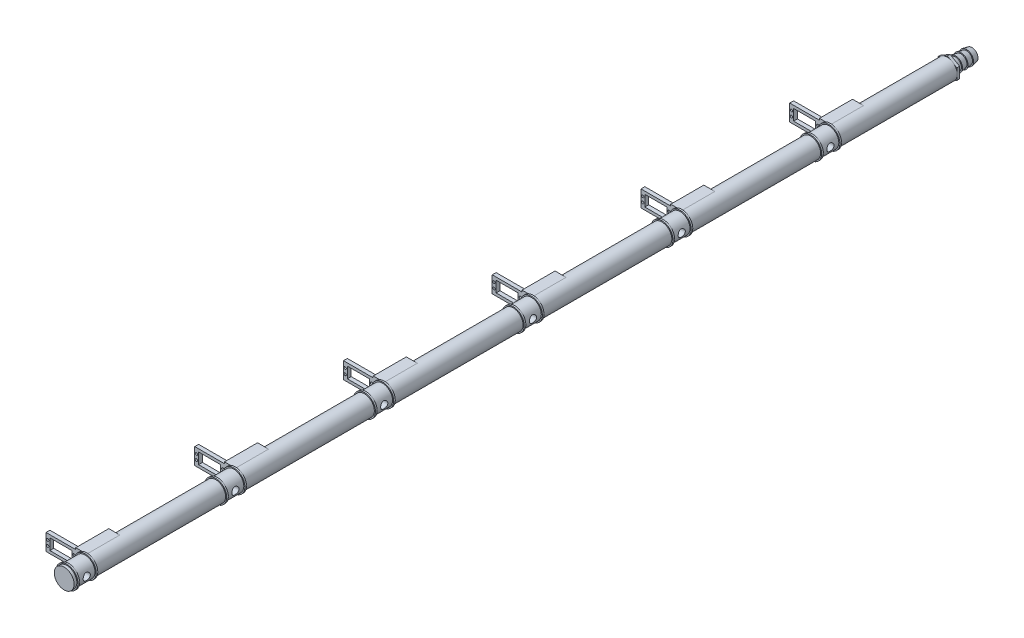
SolidWorks part; units mm, degrees
ref_plane "Front Plane" through (0, 0, 0) normal (0, 0, 1) x (1, 0, 0)
ref_plane "Top Plane" through (0, 0, 0) normal (0, 1, 0) x (1, 0, 0)
ref_plane "Right Plane" through (0, 0, 0) normal (1, 0, 0) x (0, 0, -1)
sketch "Sketch1" plane through (0, 0, 0) normal (0, 0, 1) x (1, 0, 0)
  circle A0 centre (0, 0) radius 15
  circle A1 centre (0, 0) radius 18
extrude "Boss-Extrude1" add sketch "Sketch1" along normal blind 1600
sketch "Sketch2" plane through (0, 0, 1600) normal (0, 0, 1) x (1, 0, 0)
  circle A0 centre (0, 0) radius 18
extrude "Boss-Extrude2" add sketch "Sketch2" along normal blind 3
sketch "Sketch3" plane through (0, 0, 0) normal (1, 0, 0) x (0, 0, -1)
  line L0 (-1603, 0) -> (-1600, 0) construction
  line L1 (-1603, 18) -> (-1603, -18) construction
  line L2 (-1600, 0) -> (-1600, 28.0213) construction
  line L3 (-1600, 0) -> (-100, 0) construction
  line L4 (-1600, 0) -> (-1580, 0) construction
  circle A0 centre (-1580, 0) radius 10
  circle A1 centre (-1310, 0) radius 10
  circle A2 centre (-1040, 0) radius 10
  circle A3 centre (-770, 0) radius 10
  circle A4 centre (-500, 0) radius 10
  circle A5 centre (-230, 0) radius 10
  dimension "D2" = 6
  dimension "D1" = 20
extrude "Cut-Extrude1" cut sketch "Sketch3" along normal through all
sketch "Sketch4" plane through (0, 0, 0) normal (1, 0, 0) x (0, 0, -1)
  line L0 (-1580, 0) -> (-1598, 0) construction
  line L2 (-1600, 0) -> (-100, 0) construction
  line L3 (-1598, 0) -> (-1562, 0) construction
ref_plane "Plane1" through (0, 0, 1598) normal (0, 0, 1) x (1, 0, 0)
sketch "Sketch5" plane through (0, 0, 1598) normal (0, 0, 1) x (1, 0, 0)
  circle A0 centre (0, 0) radius 18
  circle A1 centre (0, 0) radius 20
extrude "Boss-Extrude3" add sketch "Sketch5" against normal blind 3
pattern_linear "LPattern1" count 6 spacing 270 along (0, 0, -1) of "Boss-Extrude3"
ref_plane "Plane2" through (0, 0, 1562) normal (0, 0, 1) x (1, 0, 0)
sketch "Sketch6" plane through (0, 0, 1562) normal (0, 0, 1) x (1, 0, 0)
  circle A0 centre (0, 0) radius 20 construction
  circle A1 centre (0, 0) radius 20
  circle A2 centre (0, 0) radius 18 construction
  circle A3 centre (0, 0) radius 18
extrude "Boss-Extrude4" add sketch "Sketch6" along normal blind 3
pattern_linear "LPattern2" count 6 spacing 270 along (0, 0, -1) of "Boss-Extrude4"
sketch "Sketch7" plane through (0, 0, 0) normal (0, 0, -1) x (-1, 0, 0)
  line L1 (0, 20) -> (-17.3205, 10)
  line L2 (-17.3205, 10) -> (-17.3205, -10)
  line L3 (-17.3205, -10) -> (0, -20)
  line L4 (0, -20) -> (17.3205, -10)
  line L5 (17.3205, -10) -> (17.3205, 10)
  line L6 (17.3205, 10) -> (0, 20)
  circle A0 centre (0, 0) radius 17.3205 construction
extrude "Boss-Extrude5" add sketch "Sketch7" along normal blind 5 separate body
sketch "Sketch8" plane through (0, 0, 0) normal (1, 0, 0) x (0, 0, -1)
  line L0 (5, 0) -> (44.7107, 0) construction
  line L1 (5, 10) -> (5, -10) construction
  line L2 (44.7107, 0) -> (44.7107, 6) construction
  line L3 (44.7107, 6) -> (5, 6)
  line L4 (44.7107, 6) -> (44.7107, 11)
  line L5 (44.7107, 11) -> (34.7107, 11) construction
  line L6 (34.7107, 11) -> (34.7107, 13) construction
  line L7 (44.7107, 11) -> (34.7107, 13)
  line L8 (34.7107, 13) -> (34.7107, 11)
  line L9 (34.7107, 11) -> (24.7107, 13)
  line L10 (24.7107, 13) -> (24.7107, 11)
  line L11 (24.7107, 11) -> (14.7107, 13)
  line L12 (14.7107, 13) -> (14.7107, 11)
  line L13 (14.7107, 11) -> (5, 12.9421)
  line L15 (5, 6) -> (5, 12.9421)
  line L16 (5, 20) -> (5, 10) construction
  line L18 (4.7107, 13) -> (4.7107, 11) [skipped]
  dimension "D1" = 4
revolve "Revolve2" add sketch "Sketch8" angle 360 about L0
ref_plane "Plane4" through (-18, 0, 0) normal (1, 0, 0) x (0, 0, -1)
sketch "Sketch12" plane through (-18, 0, 0) normal (1, 0, 0) x (0, 0, -1)
  line L0 (-1562, 19.8) -> (-1562, -19.8) construction
  line L1 (-1562, 18) -> (-1512, 18)
  line L2 (-1562, 18) -> (-1562, -18)
  line L3 (-1562, -18) -> (-1512, -18)
  line L4 (-1512, 18) -> (-1512, -18)
  line L5 (-1328, 18) -> (-1562, 18) construction
  line L6 (-1562, -18) -> (-1328, -18) construction
  dimension "D1" = 50
sketch "Sketch13" plane through (0, 0, 1562) normal (0, 0, 1) x (1, 0, 0)
  line L0 (0, 18) -> (0, 20)
  line L1 (-18, 20) -> (18, 20)
  line L2 (18, 20) -> (18, 0)
  line L3 (-18, 20) -> (-18, 0)
  arc A0 (18, 0) -> (-18, 0) centre (0, 0) ccw
  circle A1 centre (0, 0) radius 20 construction
sketch "Sketch14" plane through (0, 0, 1562) normal (0, 0, 1) x (1, 0, 0)
  line L0 (-18, 0) -> (-20.0028, 0)
  line L1 (-20.0028, -18) -> (-20.0028, 18)
  line L2 (-20.0028, 18) -> (0, 18)
  line L3 (-20.0028, -18) -> (0, -18)
  arc A0 (0, 18) -> (0, -18) centre (0, 0) ccw
extrude "Boss-Extrude6" add sketch "Sketch14" against normal blind 60 contours A0 L2 L1 L0 | A0 L0 L1 L3
pattern_linear "LPattern3" count 6 spacing 270 along (0, 0, -1) of "Boss-Extrude6"
sketch "Sketch15" plane through (0, 0, 1562) normal (0, 0, 1) x (1, 0, 0)
  line L0 (-20, 0) -> (-47, 0) construction
  line L1 (-20, 0) -> (-20.0028, 4.85) construction
  line L2 (-20.0028, -18) -> (-20.0028, 18) construction
  line L3 (-20.0028, 4.85) -> (-23.0028, 4.85) construction
  line L4 (-47, 0) -> (-47, 13.2216) construction
  line L5 (-20, 0) -> (-27, 0)
  line L6 (-20, 0) -> (-20, 15) construction
  line L7 (-67, -10) -> (-27, -10)
  line L8 (-67, -10) -> (-67, 10)
  line L9 (-67, 10) -> (-27, 10)
  line L10 (-27, -10) -> (-27, 10)
  line L11 (-67, -10) -> (-27, 10) construction
  line L12 (-67, 10) -> (-27, -10) construction
  line L14 (-74, -15) -> (-20, -15)
  line L15 (-74, -15) -> (-74, 15)
  line L16 (-74, 15) -> (-20, 15)
  line L17 (-20, -15) -> (-20, 15)
  line L18 (-74, -15) -> (-20, 15) construction
  line L19 (-74, 15) -> (-20, -15) construction
  circle A0 centre (0, 0) radius 20 construction
  circle A1 centre (-23.0028, 4.85) radius 2.15
  circle A2 centre (-23.0028, -4.85) radius 2.15
  circle A3 centre (-70.9972, -4.85) radius 2.15
  circle A4 centre (-70.9972, 4.85) radius 2.15
extrude "Boss-Extrude7" add sketch "Sketch15" against normal blind 7
pattern_linear "LPattern4" count 6 spacing 270 along (0, 0, -1) of "Boss-Extrude7"
sketch "Sketch18" plane through (0, 0, 205) normal (0, 0, -1) x (-1, 0, 0)
  line L0 (27, -10) -> (20.0028, -10) construction
  line L1 (20.0028, 15) -> (20.0028, -15) construction
sketch "Sketch20" plane through (0, 0, 0) normal (0, 0, -1) x (-1, 0, 0)
  circle A1 centre (0, 0) radius 7.5
  circle A2 centre (0, 0) radius 18
extrude "Boss-Extrude8" add sketch "Sketch20" against normal up to next
sketch "Sketch21" plane through (0, 0, 0) normal (1, 0, 0) x (0, 0, -1)
  circle A1 centre (-1040, 0) radius 10
  circle A2 centre (-1040, 0) radius 10
  circle A3 centre (-1310, 0) radius 10
  circle A4 centre (-1310, 0) radius 10
  circle A5 centre (-1580, 0) radius 10
  circle A6 centre (-1580, 0) radius 10
  circle A7 centre (-230, 0) radius 10
  circle A8 centre (-230, 0) radius 10
  circle A9 centre (-500, 0) radius 10
  circle A10 centre (-500, 0) radius 10
  circle A11 centre (-770, 0) radius 10
  circle A12 centre (-770, 0) radius 10
  dimension "D1" = 0
  dimension "D2" = 0
  dimension "D3" = 0
  dimension "D4" = 0
  dimension "D5" = 0
  dimension "D6" = 0
sketch "Sketch22" plane through (0, 0, 0) normal (1, 0, 0) x (0, 0, -1)
  circle A2 centre (-1580, 0) radius 6.5
  circle A3 centre (-1310, 0) radius 6.5
  circle A4 centre (-1040, 0) radius 6.5
  circle A5 centre (-770, 0) radius 6.5
  circle A6 centre (-500, 0) radius 6.5
  circle A7 centre (-230, 0) radius 6.5
  dimension "D1" = 6
extrude "Cut-Extrude4" cut sketch "Sketch22" along normal blind 20
sketch "Sketch23" plane through (0, 0, -5) normal (0, 0, -1) x (-1, 0, 0)
  circle A0 centre (0, 0) radius 6
extrude "Cut-Extrude5" cut sketch "Sketch23" against normal blind 30
